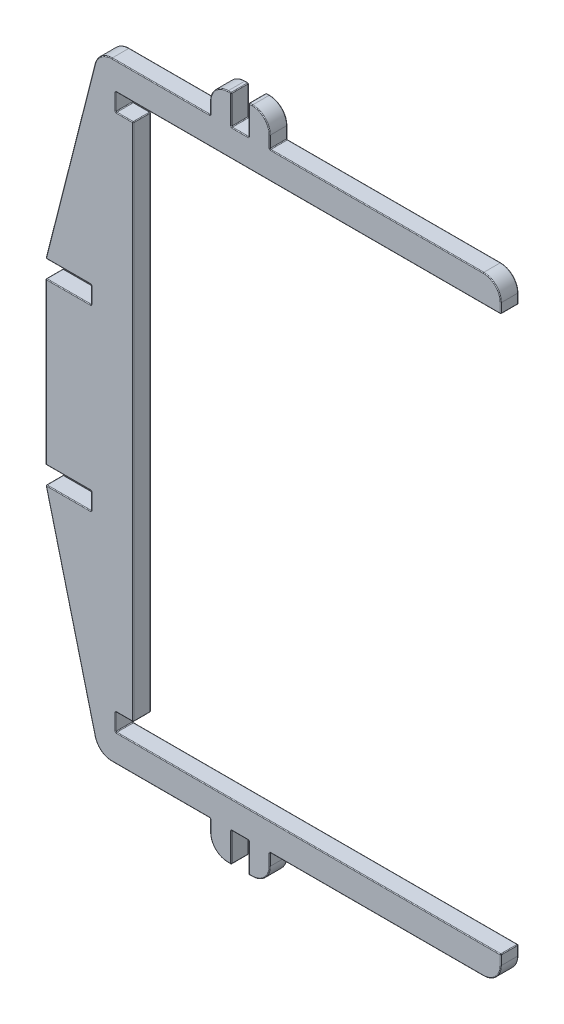
SolidWorks part; units mm, degrees
ref_plane "Plano frontal" through (0, 0, 0) normal (0, 0, 1) x (1, 0, 0)
ref_plane "Plano superior" through (0, 0, 0) normal (0, 1, 0) x (1, 0, 0)
ref_plane "Plano direito" through (0, 0, 0) normal (1, 0, 0) x (0, 0, -1)
sketch "Esboço1" plane through (0, 0, 0) normal (0, 0, 1) x (1, 0, 0)
  line L153 (136.2066, 157.6811) -> (129.1856, 130.0651)
  line L154 (138.6295, 159.5651) -> (191.6856, 159.5651)
  line L155 (136.6856, 159.5651) -> (136.6856, 72.5651) construction
  line L156 (138.6295, 72.5651) -> (191.6856, 72.5651)
  line L157 (194.1856, 157.0651) -> (194.1856, 75.0651)
  line L158 (139.1856, 155.6651) -> (194.1856, 155.6651)
  line L159 (139.1856, 155.6651) -> (139.1856, 76.4651)
  line L160 (139.1856, 76.4651) -> (194.1856, 76.4651)
  line L161 (194.1856, 155.6651) -> (194.1856, 76.4651)
  line L162 (139.1856, 153.1651) -> (141.6856, 153.1651)
  line L163 (139.1856, 153.1651) -> (139.1856, 78.9651)
  line L164 (139.1856, 78.9651) -> (141.6856, 78.9651)
  line L165 (141.6856, 153.1651) -> (141.6856, 78.9651)
  line L166 (129.1856, 130.0651) -> (129.1856, 102.0651)
  line L167 (129.1856, 102.0651) -> (136.2066, 74.4491)
  line L169 (129.1856, 130.0651) -> (135.6856, 130.0651)
  line L170 (129.1856, 130.0651) -> (129.1856, 127.5651)
  line L171 (129.1856, 127.5651) -> (135.6856, 127.5651)
  line L172 (135.6856, 130.0651) -> (135.6856, 127.5651)
  line L173 (129.1856, 102.0651) -> (135.6856, 102.0651)
  line L174 (129.1856, 102.0651) -> (129.1856, 104.5651)
  line L175 (129.1856, 104.5651) -> (135.6856, 104.5651)
  line L176 (135.6856, 102.0651) -> (135.6856, 104.5651)
  line L177 (152.6856, 159.5651) -> (155.6856, 159.5651)
  line L178 (152.6856, 159.5651) -> (152.6856, 161.286)
  line L179 (155.1856, 163.786) -> (155.6856, 163.786)
  line L180 (155.6856, 159.5651) -> (155.6856, 163.786)
  line L181 (158.1856, 159.5651) -> (161.1856, 159.5651)
  line L182 (158.1856, 159.5651) -> (158.1856, 163.786)
  line L183 (158.1856, 163.786) -> (158.6856, 163.786)
  line L184 (161.1856, 159.5651) -> (161.1856, 161.286)
  line L185 (161.1856, 72.5651) -> (158.1856, 72.5651)
  line L186 (161.1856, 72.5651) -> (161.1856, 70.8442)
  line L187 (158.6856, 68.3442) -> (158.1856, 68.3442)
  line L188 (158.1856, 72.5651) -> (158.1856, 68.3442)
  line L189 (155.6856, 72.5651) -> (152.6856, 72.5651)
  line L190 (155.6856, 72.5651) -> (155.6856, 68.3442)
  line L191 (155.6856, 68.3442) -> (155.1856, 68.3442)
  line L192 (152.6856, 72.5651) -> (152.6856, 70.8442)
  arc A22 (191.6856, 72.5651) -> (194.1856, 75.0651) centre (191.6856, 75.0651) ccw
  arc A23 (191.6856, 159.5651) -> (194.1856, 157.0651) centre (191.6856, 157.0651) cw
  arc A24 (136.2066, 74.4491) -> (138.6295, 72.5651) centre (138.6295, 75.0651) ccw
  arc A25 (138.6295, 159.5651) -> (136.2066, 157.6811) centre (138.6295, 157.0651) ccw
  arc A26 (155.1856, 68.3442) -> (152.6856, 70.8442) centre (155.1856, 70.8442) cw
  arc A27 (161.1856, 70.8442) -> (158.6856, 68.3442) centre (158.6856, 70.8442) cw
  arc A28 (152.6856, 161.286) -> (155.1856, 163.786) centre (155.1856, 161.286) cw
  arc A29 (158.6856, 163.786) -> (161.1856, 161.286) centre (158.6856, 161.286) cw
  point P279 (139.1856, 116.0651)
  dimension "D1" = 5
  dimension "D86" = 2.5
  dimension "D91" = 2.5
  dimension "D2" = 12.5
  dimension "D3" = 1
  dimension "D4" = 1
  dimension "D78" = 79.2
  dimension "D79" = 3.9
  dimension "D80" = 2.5
  dimension "D81" = 2.5
  dimension "D82" = 52.5
  dimension "D83" = 2.5
  dimension "D84" = 28
  dimension "D85" = 14
  dimension "D87" = 2.5
  dimension "D88" = 2.5
  dimension "D90" = 2.5
  dimension "D92" = 2.5
extrude "Ressalto-extrusão1" add sketch "Esboço1" along normal blind 2.5 contours L155 A25 L153 L169 L172 L171 L166 L175 L176 L173 L167 A24 | A25 L155 A24 L156 A22 L157 L160 L159 L158 A23 L154 | L165 L162 L159 L164 | A29 L183 L182 L154 L184 | A28 L178 L154 L180 L179 | A27 L186 L156 L188 L187 | A26 L191 L190 L156 L192
fillet "Filete1" radius 0.1 116 edges at (152.6856, 72.5651, 1.25) (155.6856, 68.3442, 1.25) (155.6856, 72.5651, 1.25) (158.1856, 72.5651, 1.25) (158.1856, 68.3442, 1.25) (161.1856, 72.5651, 1.25) (194.1856, 76.4651, 1.25) (139.1856, 76.4651, 1.25) (139.1856, 78.9651, 1.25) (141.6856, 78.9651, 1.25) (141.6856, 153.1651, 1.25) (139.1856, 153.1651, 1.25) (139.1856, 155.6651, 1.25) (194.1856, 155.6651, 1.25) (161.1856, 159.5651, 1.25) (158.1856, 163.786, 1.25) (158.1856, 159.5651, 1.25) (155.6856, 159.5651, 1.25) (155.6856, 163.786, 1.25) (152.6856, 159.5651, 1.25) (129.1856, 130.0651, 1.25) (135.6856, 130.0651, 1.25) (135.6856, 127.5651, 1.25) (129.1856, 127.5651, 1.25) (129.1856, 104.5651, 1.25) (135.6856, 104.5651, 1.25) (135.6856, 102.0651, 1.25) (129.1856, 102.0651, 1.25) (132.6961, 88.2571, 0) (132.6961, 88.2571, 2.5) (132.4356, 102.0651, 0) (132.4356, 102.0651, 2.5) (135.6856, 103.3151, 0) (135.6856, 103.3151, 2.5) (132.4356, 104.5651, 0) (132.4356, 104.5651, 2.5) (129.1856, 116.0651, 0) (129.1856, 116.0651, 2.5) (132.4356, 127.5651, 0) (132.4356, 127.5651, 2.5) (135.6856, 128.8151, 0) (135.6856, 128.8151, 2.5) (132.4356, 130.0651, 0) (132.4356, 130.0651, 2.5) (132.6961, 143.8731, 0) (132.6961, 143.8731, 2.5) (137.0949, 159.0387, 0) (137.0949, 159.0387, 2.5) (145.6575, 159.5651, 2.5) (145.6575, 159.5651, 0) (152.6856, 160.4255, 0) (152.6856, 160.4255, 2.5) (153.4178, 163.0537, 0) (153.4178, 163.0537, 2.5) (155.4356, 163.786, 0) (155.4356, 163.786, 2.5) (155.6856, 161.6755, 0) (155.6856, 161.6755, 2.5) (156.9356, 159.5651, 2.5) (156.9356, 159.5651, 0) (158.1856, 161.6755, 0) (158.1856, 161.6755, 2.5) (158.4356, 163.786, 0) (158.4356, 163.786, 2.5) (160.4533, 163.0537, 0) (160.4533, 163.0537, 2.5) (161.1856, 160.4255, 0) (161.1856, 160.4255, 2.5) (176.4356, 159.5651, 2.5) (176.4356, 159.5651, 0) (193.4533, 158.8329, 0) (193.4533, 158.8329, 2.5) (194.1856, 156.3651, 0) (194.1856, 156.3651, 2.5) (166.6856, 155.6651, 0) (166.6856, 155.6651, 2.5) (139.1856, 154.4151, 0) (139.1856, 154.4151, 2.5) (140.4356, 153.1651, 0) (140.4356, 153.1651, 2.5) (141.6856, 116.0651, 0) (141.6856, 116.0651, 2.5) (140.4356, 78.9651, 0) (140.4356, 78.9651, 2.5) (139.1856, 77.7151, 0) (139.1856, 77.7151, 2.5) (166.6856, 76.4651, 0) (166.6856, 76.4651, 2.5) (194.1856, 75.7651, 0) (194.1856, 75.7651, 2.5) (193.4533, 73.2973, 0) (193.4533, 73.2973, 2.5) (176.4356, 72.5651, 2.5) (176.4356, 72.5651, 0) (161.1856, 71.7046, 0) (161.1856, 71.7046, 2.5) (160.4533, 69.0764, 0) (160.4533, 69.0764, 2.5) (158.4356, 68.3442, 0) (158.4356, 68.3442, 2.5) (158.1856, 70.4546, 0) (158.1856, 70.4546, 2.5) (156.9356, 72.5651, 2.5) (156.9356, 72.5651, 0) (155.6856, 70.4546, 0) (155.6856, 70.4546, 2.5) (155.4356, 68.3442, 0) (155.4356, 68.3442, 2.5) (153.4178, 69.0764, 0) (153.4178, 69.0764, 2.5) (152.6856, 71.7046, 0) (152.6856, 71.7046, 2.5) (145.6575, 72.5651, 2.5) (145.6575, 72.5651, 0) (137.0949, 73.0915, 0) (137.0949, 73.0915, 2.5)
